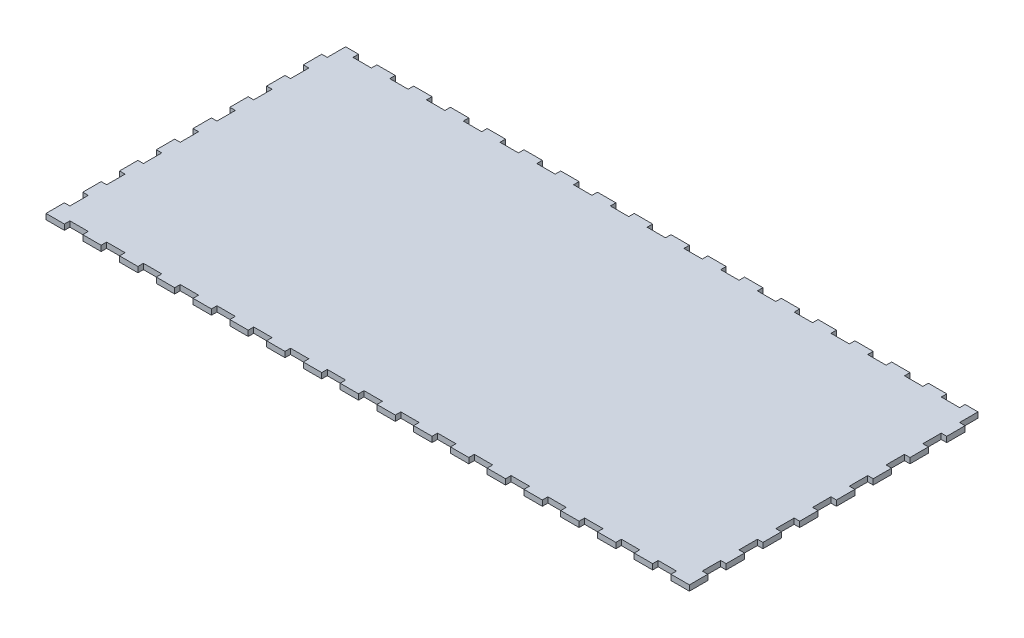
SolidWorks part; units mm, degrees
ref_plane "Alzado" through (0, 0, 0) normal (0, 0, 1) x (1, 0, 0)
ref_plane "Planta" through (0, 0, 0) normal (0, 1, 0) x (1, 0, 0)
ref_plane "Vista lateral" through (0, 0, 0) normal (1, 0, 0) x (0, 0, -1)
sketch "Croquis1" plane through (0, 0, 0) normal (0, 1, 0) x (1, 0, 0)
  line L0 (165, -80) -> (175, -80)
  line L1 (-55, 0) -> (51.2469, 0) construction
  line L2 (0, 30) -> (0, -35.1141) construction
  line L3 (175, -80) -> (175, -70)
  line L5 (175, -80) -> (-175, 80) construction
  line L6 (175, 80) -> (-175, -80) construction
  line L7 (165, -77) -> (165, -80)
  line L8 (155, -77) -> (165, -77)
  line L9 (155, -80) -> (155, -77)
  line L10 (145, -80) -> (155, -80)
  line L11 (145, -77) -> (145, -80)
  line L12 (135, -77) -> (145, -77)
  line L13 (135, -80) -> (135, -77)
  line L14 (125, -80) -> (135, -80)
  line L15 (125, -77) -> (125, -80)
  line L16 (115, -77) -> (125, -77)
  line L17 (115, -80) -> (115, -77)
  line L18 (105, -80) -> (115, -80)
  line L19 (105, -77) -> (105, -80)
  line L20 (95, -77) -> (105, -77)
  line L21 (95, -80) -> (95, -77)
  line L22 (85, -80) -> (95, -80)
  line L23 (85, -77) -> (85, -80)
  line L24 (75, -77) -> (85, -77)
  line L25 (75, -80) -> (75, -77)
  line L26 (65, -80) -> (75, -80)
  line L27 (65, -77) -> (65, -80)
  line L28 (55, -77) -> (65, -77)
  line L29 (55, -80) -> (55, -77)
  line L30 (45, -80) -> (55, -80)
  line L31 (45, -77) -> (45, -80)
  line L32 (35, -77) -> (45, -77)
  line L33 (35, -80) -> (35, -77)
  line L34 (25, -80) -> (35, -80)
  line L35 (25, -77) -> (25, -80)
  line L36 (15, -77) -> (25, -77)
  line L37 (15, -80) -> (15, -77)
  line L38 (5, -80) -> (15, -80)
  line L39 (5, -77) -> (5, -80)
  line L40 (-5, -77) -> (5, -77)
  line L41 (-5, -80) -> (-5, -77)
  line L42 (-15, -80) -> (-5, -80)
  line L43 (-15, -77) -> (-15, -80)
  line L44 (-25, -77) -> (-15, -77)
  line L45 (-25, -80) -> (-25, -77)
  line L46 (-35, -80) -> (-25, -80)
  line L47 (-35, -77) -> (-35, -80)
  line L48 (-45, -77) -> (-35, -77)
  line L49 (-45, -80) -> (-45, -77)
  line L50 (-55, -80) -> (-45, -80)
  line L51 (-55, -77) -> (-55, -80)
  line L52 (-65, -77) -> (-55, -77)
  line L53 (-65, -80) -> (-65, -77)
  line L54 (-75, -80) -> (-65, -80)
  line L55 (-75, -77) -> (-75, -80)
  line L56 (-85, -77) -> (-75, -77)
  line L57 (-85, -80) -> (-85, -77)
  line L58 (-95, -80) -> (-85, -80)
  line L59 (-95, -77) -> (-95, -80)
  line L60 (-105, -77) -> (-95, -77)
  line L61 (-105, -80) -> (-105, -77)
  line L62 (-115, -80) -> (-105, -80)
  line L63 (-115, -77) -> (-115, -80)
  line L64 (-125, -77) -> (-115, -77)
  line L65 (-125, -80) -> (-125, -77)
  line L66 (-135, -80) -> (-125, -80)
  line L67 (-135, -77) -> (-135, -80)
  line L68 (-145, -77) -> (-135, -77)
  line L69 (-155, -77) -> (-155, -80)
  line L70 (-165, -77) -> (-155, -77)
  line L71 (-165, -80) -> (-165, -77)
  line L72 (-145, -80) -> (-145, -77)
  line L73 (-155, -80) -> (-145, -80)
  line L74 (-175, -80) -> (-165, -80)
  line L75 (-172, 80) -> (-165, 80)
  line L76 (-155, 80) -> (-145, 80)
  line L77 (-145, 80) -> (-145, 77)
  line L78 (-165, 80) -> (-165, 77)
  line L79 (-165, 77) -> (-155, 77)
  line L80 (-155, 77) -> (-155, 80)
  line L81 (-145, 77) -> (-135, 77)
  line L82 (-135, 77) -> (-135, 80)
  line L83 (-135, 80) -> (-125, 80)
  line L84 (-125, 80) -> (-125, 77)
  line L85 (-125, 77) -> (-115, 77)
  line L86 (-115, 77) -> (-115, 80)
  line L87 (-115, 80) -> (-105, 80)
  line L88 (-105, 80) -> (-105, 77)
  line L89 (-105, 77) -> (-95, 77)
  line L90 (-95, 77) -> (-95, 80)
  line L91 (-95, 80) -> (-85, 80)
  line L92 (-85, 80) -> (-85, 77)
  line L93 (-85, 77) -> (-75, 77)
  line L94 (-75, 77) -> (-75, 80)
  line L95 (-75, 80) -> (-65, 80)
  line L96 (-65, 80) -> (-65, 77)
  line L97 (-65, 77) -> (-55, 77)
  line L98 (-55, 77) -> (-55, 80)
  line L99 (-55, 80) -> (-45, 80)
  line L100 (-45, 80) -> (-45, 77)
  line L101 (-45, 77) -> (-35, 77)
  line L102 (-35, 77) -> (-35, 80)
  line L103 (-35, 80) -> (-25, 80)
  line L104 (-25, 80) -> (-25, 77)
  line L105 (-25, 77) -> (-15, 77)
  line L106 (-15, 77) -> (-15, 80)
  line L107 (-15, 80) -> (-5, 80)
  line L108 (-5, 80) -> (-5, 77)
  line L109 (-5, 77) -> (5, 77)
  line L110 (5, 77) -> (5, 80)
  line L111 (5, 80) -> (15, 80)
  line L112 (15, 80) -> (15, 77)
  line L113 (15, 77) -> (25, 77)
  line L114 (25, 77) -> (25, 80)
  line L115 (25, 80) -> (35, 80)
  line L116 (35, 80) -> (35, 77)
  line L117 (35, 77) -> (45, 77)
  line L118 (45, 77) -> (45, 80)
  line L119 (45, 80) -> (55, 80)
  line L120 (55, 80) -> (55, 77)
  line L121 (55, 77) -> (65, 77)
  line L122 (65, 77) -> (65, 80)
  line L123 (65, 80) -> (75, 80)
  line L124 (75, 80) -> (75, 77)
  line L125 (75, 77) -> (85, 77)
  line L126 (85, 77) -> (85, 80)
  line L127 (85, 80) -> (95, 80)
  line L128 (95, 80) -> (95, 77)
  line L129 (95, 77) -> (105, 77)
  line L130 (105, 77) -> (105, 80)
  line L131 (105, 80) -> (115, 80)
  line L132 (115, 80) -> (115, 77)
  line L133 (115, 77) -> (125, 77)
  line L134 (125, 77) -> (125, 80)
  line L135 (125, 80) -> (135, 80)
  line L136 (135, 80) -> (135, 77)
  line L137 (135, 77) -> (145, 77)
  line L138 (145, 77) -> (145, 80)
  line L139 (145, 80) -> (155, 80)
  line L140 (155, 80) -> (155, 77)
  line L141 (155, 77) -> (165, 77)
  line L142 (165, 77) -> (165, 80)
  line L143 (165, 80) -> (172, 80)
  line L144 (175, -60) -> (175, -50)
  line L145 (175, -70) -> (172, -70)
  line L146 (172, -70) -> (172, -60)
  line L147 (172, -60) -> (175, -60)
  line L148 (172, -50) -> (172, -40)
  line L149 (175, -50) -> (172, -50)
  line L150 (172, -40) -> (175, -40)
  line L151 (175, -40) -> (175, -30)
  line L152 (172, -30) -> (172, -20)
  line L153 (175, -30) -> (172, -30)
  line L154 (172, -20) -> (175, -20)
  line L155 (175, -20) -> (175, -10)
  line L156 (172, -10) -> (172, 0)
  line L157 (175, -10) -> (172, -10)
  line L158 (172, 0) -> (175, 0)
  line L159 (175, 0) -> (175, 10)
  line L160 (172, 10) -> (172, 20)
  line L161 (175, 10) -> (172, 10)
  line L162 (172, 20) -> (175, 20)
  line L163 (175, 20) -> (175, 30)
  line L164 (172, 30) -> (172, 40)
  line L165 (175, 30) -> (172, 30)
  line L166 (172, 40) -> (175, 40)
  line L167 (175, 40) -> (175, 50)
  line L168 (172, 50) -> (172, 60)
  line L169 (175, 50) -> (172, 50)
  line L170 (172, 60) -> (175, 60)
  line L171 (175, 60) -> (175, 70)
  line L172 (172, 70) -> (172, 80)
  line L173 (175, 70) -> (172, 70)
  line L174 (-175, 70) -> (-172, 70)
  line L175 (-172, 70) -> (-172, 80)
  line L176 (-175, 60) -> (-175, 70)
  line L177 (-172, 60) -> (-175, 60)
  line L178 (-175, 50) -> (-172, 50)
  line L179 (-172, 50) -> (-172, 60)
  line L180 (-175, 40) -> (-175, 50)
  line L181 (-172, 40) -> (-175, 40)
  line L182 (-175, 30) -> (-172, 30)
  line L183 (-172, 30) -> (-172, 40)
  line L184 (-175, 20) -> (-175, 30)
  line L185 (-172, 20) -> (-175, 20)
  line L186 (-175, 10) -> (-172, 10)
  line L187 (-172, 10) -> (-172, 20)
  line L188 (-175, 0) -> (-175, 10)
  line L189 (-172, 0) -> (-175, 0)
  line L190 (-175, -10) -> (-172, -10)
  line L191 (-172, -10) -> (-172, 0)
  line L192 (-175, -20) -> (-175, -10)
  line L193 (-172, -20) -> (-175, -20)
  line L194 (-175, -30) -> (-172, -30)
  line L195 (-172, -30) -> (-172, -20)
  line L196 (-175, -40) -> (-175, -30)
  line L197 (-172, -40) -> (-175, -40)
  line L198 (-175, -50) -> (-172, -50)
  line L199 (-172, -50) -> (-172, -40)
  line L200 (-172, -60) -> (-175, -60)
  line L201 (-172, -70) -> (-172, -60)
  line L202 (-175, -70) -> (-172, -70)
  line L203 (-175, -60) -> (-175, -50)
  line L204 (-175, -80) -> (-175, -70)
  point P1 (0, 0)
  dimension "D1" = 350
  dimension "D2" = 160
extrude "Saliente-Extruir1" add sketch "Croquis1" along normal blind 3
